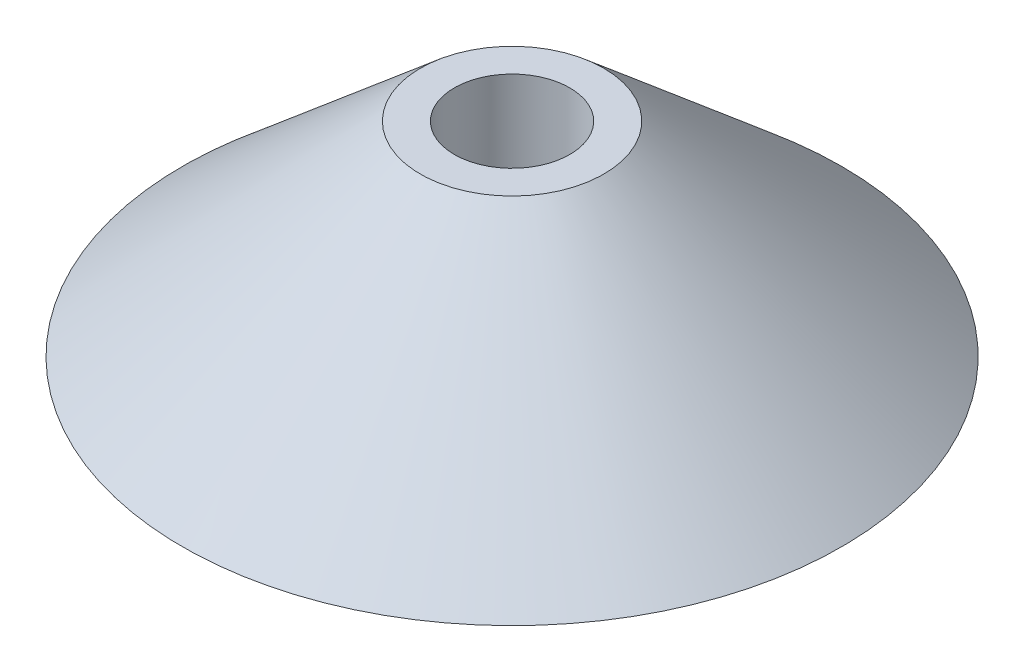
SolidWorks part; units mm, degrees
ref_plane "Ebene vorne" through (0, 0, 0) normal (0, 0, 1) x (1, 0, 0)
ref_plane "Ebene oben" through (0, 0, 0) normal (0, 1, 0) x (1, 0, 0)
ref_plane "Ebene rechts" through (0, 0, 0) normal (1, 0, 0) x (0, 0, -1)
sketch "Sketch1" plane through (0, 0, 0) normal (0, 0, 1) x (1, 0, 0)
  line L0 (0, 11.3265) -> (0, -9.4898) construction
  line L2 (-2.7, 6) -> (-9.7, 0)
  line L3 (-9.7, 0) -> (-1.7, 0)
  line L4 (-2.7, 6) -> (-1.7, 6)
  line L5 (-1.7, 6) -> (-1.7, 0)
  dimension "D1" = 6
  dimension "D2" = 1
  dimension "D3" = 3.4
  dimension "D4" = 8
revolve "Revolve1" add sketch "Sketch1" angle 360 about L0
sketch "Sketch2" plane through (0, 0, 0) normal (0, -1, 0) x (1, 0, 0)
  line L1 (1.6975, -3.0197) -> (3.4639, -0.0397)
  line L2 (3.4639, -0.0397) -> (1.7663, 2.9799)
  line L3 (1.7663, 2.9799) -> (-1.6975, 3.0197)
  line L4 (-1.6975, 3.0197) -> (-3.4639, 0.0397)
  line L5 (-3.4639, 0.0397) -> (-1.7663, -2.9799)
  line L6 (-1.7663, -2.9799) -> (1.6975, -3.0197)
  circle A0 centre (0, 0) radius 3 construction
  dimension "D1" = 6
extrude "Cut-Extrude1" cut sketch "Sketch2" against normal blind 2.5
